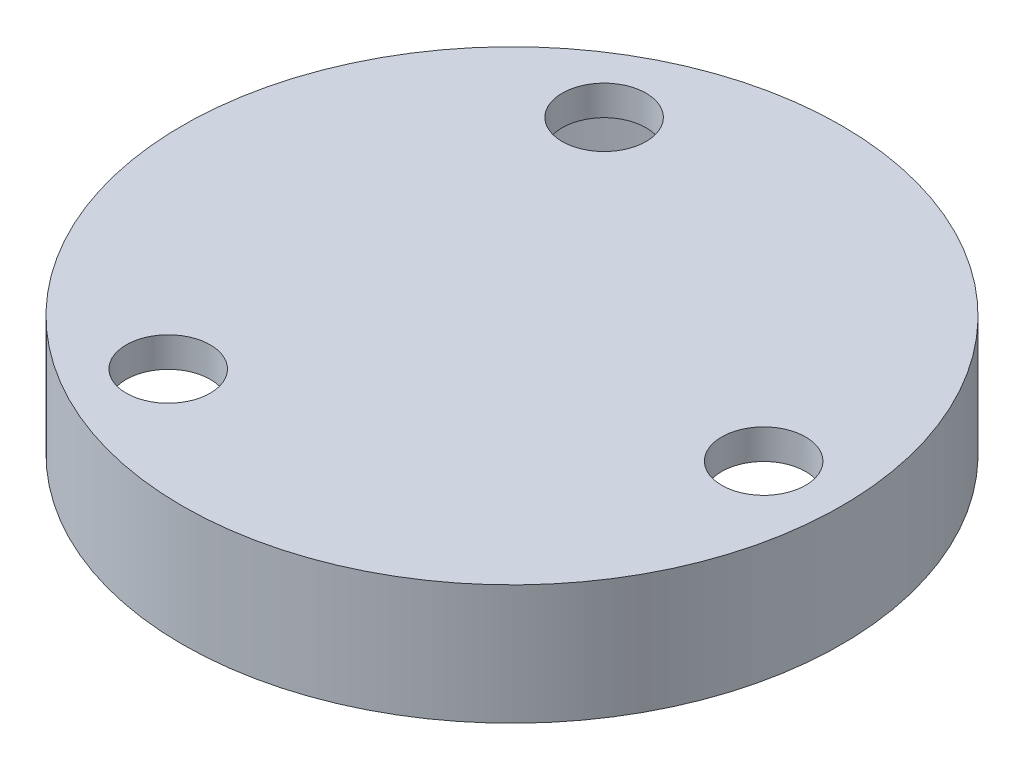
SolidWorks part; units mm, degrees
ref_plane "Front Plane" through (0, 0, 0) normal (0, 0, 1) x (1, 0, 0)
ref_plane "Top Plane" through (0, 0, 0) normal (0, 1, 0) x (1, 0, 0)
ref_plane "Right Plane" through (0, 0, 0) normal (1, 0, 0) x (0, 0, -1)
sketch "Sketch2" plane through (0, 0, 0) normal (0, 1, 0) x (1, 0, 0)
  circle A0 centre (0, 0) radius 55
  dimension "D1" = 110
extrude "Boss-Extrude1" add sketch "Sketch2" along normal blind 20
sketch "Sketch3" plane through (0, 0, 0) normal (0, -1, 0) x (1, 0, 0)
  circle A0 centre (0, 0) radius 50
  dimension "D1" = 100
extrude "Cut-Extrude1" cut sketch "Sketch3" against normal blind 15
hole_wizard "Ø1.0mm Dowel Hole1" positions "Sketch12" profile "Sketch14" hole size "Ø1.0" standard "ISO" end condition through all
sketch "Sketch12" plane through (0, 20, 0) normal (0, 1, 0) x (1, 0, 0)
  line L0 (0, 0) -> (42, 0) construction
  line L2 (0, 0) -> (-21, 36.3731) construction
  line L4 (0, 0) -> (-21, -36.3731) construction
  circle A0 centre (0, 0) radius 42 construction
  point P0 (42, 0)
  point P2 (-21, 36.3731)
  point P4 (-21, -36.3731)
  point P26 (0, 0)
  dimension "D3" = 84
  dimension "D1" = 120
  dimension "D2" = 120
sketch "Sketch14" plane through (42, 20, 0) normal (1, 0, 0) x (0, 0, 1)
  line L0 (0, 0) -> (0, 20)
  line L1 (0, 20) -> (7, 20)
  line L2 (7, 20) -> (7, 0)
  line L5 (7, 0) -> (0, 0)
  line L11 (0, -6.35) -> (0, 107.95) construction
  dimension "Thru Hole Dia." = 14
  dimension "Thru Hole Depth" = 20
